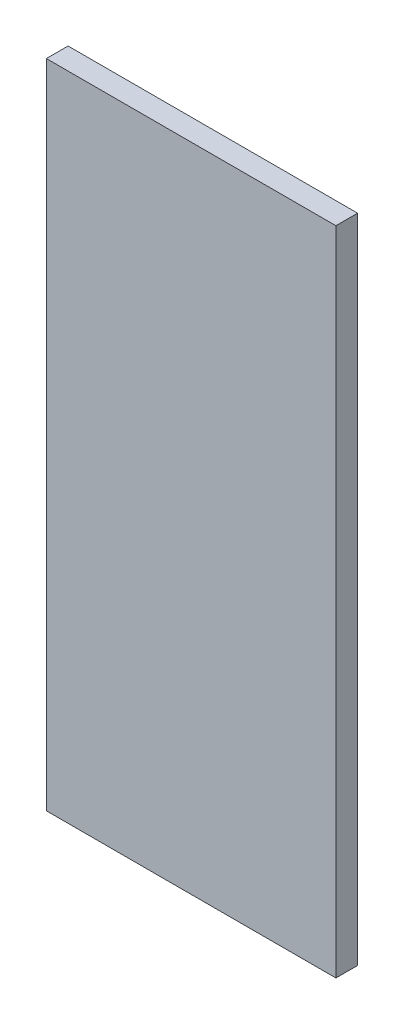
SolidWorks part; units mm, degrees
ref_plane "前视基准面" through (0, 0, 0) normal (0, 0, 1) x (1, 0, 0)
ref_plane "上视基准面" through (0, 0, 0) normal (0, 1, 0) x (1, 0, 0)
ref_plane "右视基准面" through (0, 0, 0) normal (1, 0, 0) x (0, 0, -1)
other "Configuration Table"
sketch "草图1" plane through (0, 0, 0) normal (0, 0, 1) x (1, 0, 0)
  line L0 (-20, -45) -> (20, -45)
  line L1 (20, -45) -> (20, 45)
  line L2 (20, 45) -> (-20, 45)
  line L3 (-20, 45) -> (-20, -45)
extrude "设备占位" add sketch "草图1" along normal blind 3
